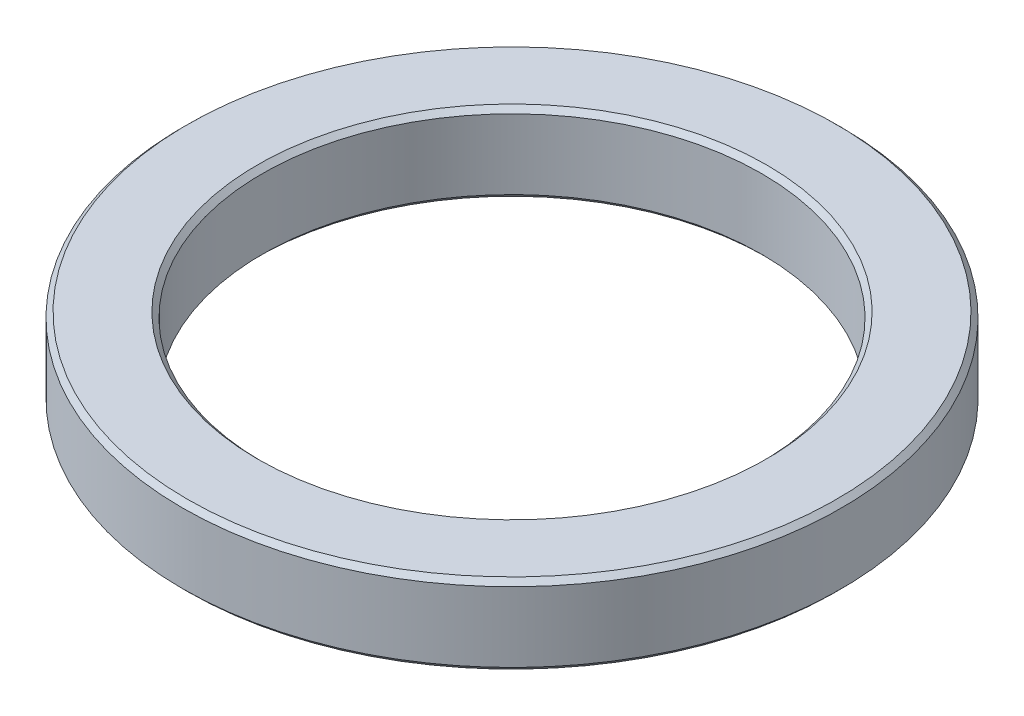
SolidWorks part; units mm, degrees
material "Wrought Stainless Steel"
ref_plane "前视基准面" through (0, 0, 0) normal (0, 0, 1) x (1, 0, 0)
ref_plane "上视基准面" through (0, 0, 0) normal (0, 1, 0) x (1, 0, 0)
ref_plane "右视基准面" through (0, 0, 0) normal (1, 0, 0) x (0, 0, -1)
other "Configuration Table"
sketch "草图2" plane through (0, 0, 0) normal (0, 1, 0) x (1, 0, 0)
  circle A0 centre (0, 0) radius 25
  circle A1 centre (0, 0) radius 33
  dimension "D1" = 50
  dimension "D2" = 66
extrude "凸台-拉伸1" add sketch "草图2" along normal mid plane 8
chamfer "倒角1" distance 0.5 angle 45 4 edges at (0, -4, 25) (0, -4, 33) (0, 4, 25) (0, 4, 33)
